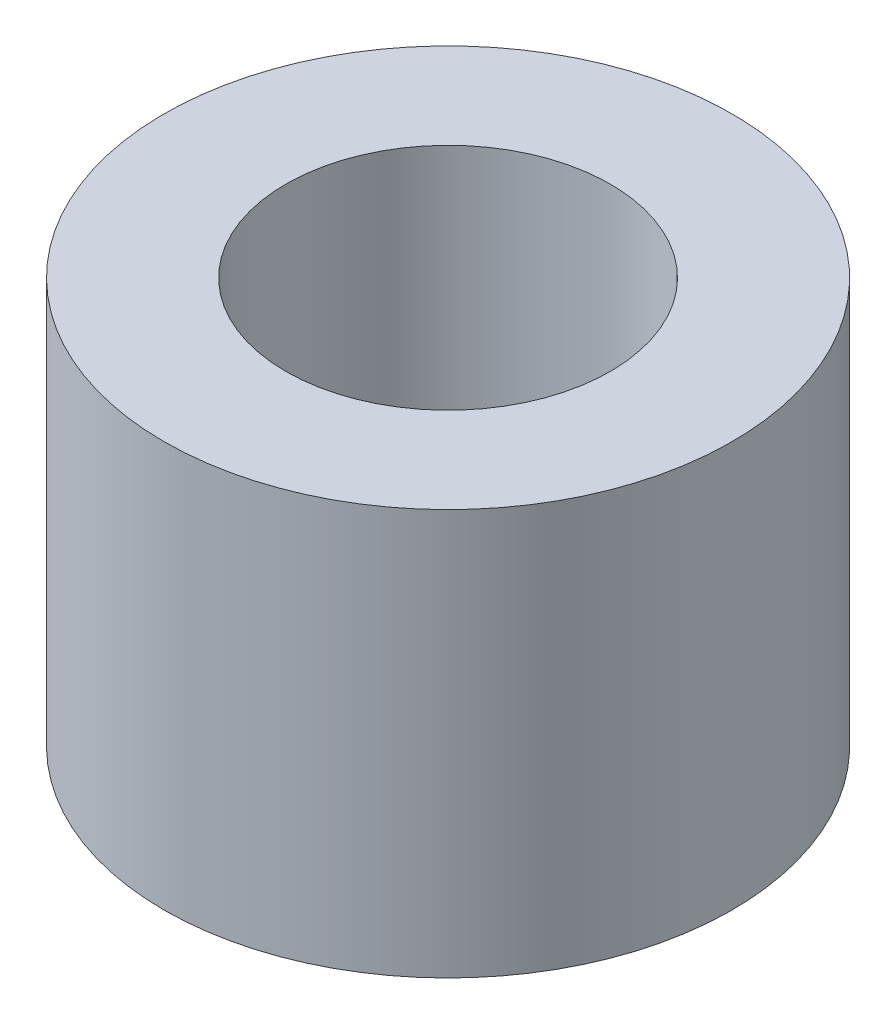
SolidWorks part; units mm, degrees
material "尼龙 101"
ref_plane "前视基准面" through (0, 0, 0) normal (0, 0, 1) x (1, 0, 0)
ref_plane "上视基准面" through (0, 0, 0) normal (0, 1, 0) x (1, 0, 0)
ref_plane "右视基准面" through (0, 0, 0) normal (1, 0, 0) x (0, 0, -1)
sketch "草图1" plane through (0, 0, 0) normal (0, 1, 0) x (1, 0, 0)
  circle A0 centre (0, 0) radius 3.5
  circle A1 centre (0, 0) radius 2
  dimension "D1" = 4
  dimension "D2" = 7
extrude "凸台-拉伸1" add sketch "草图1" along normal blind 5
